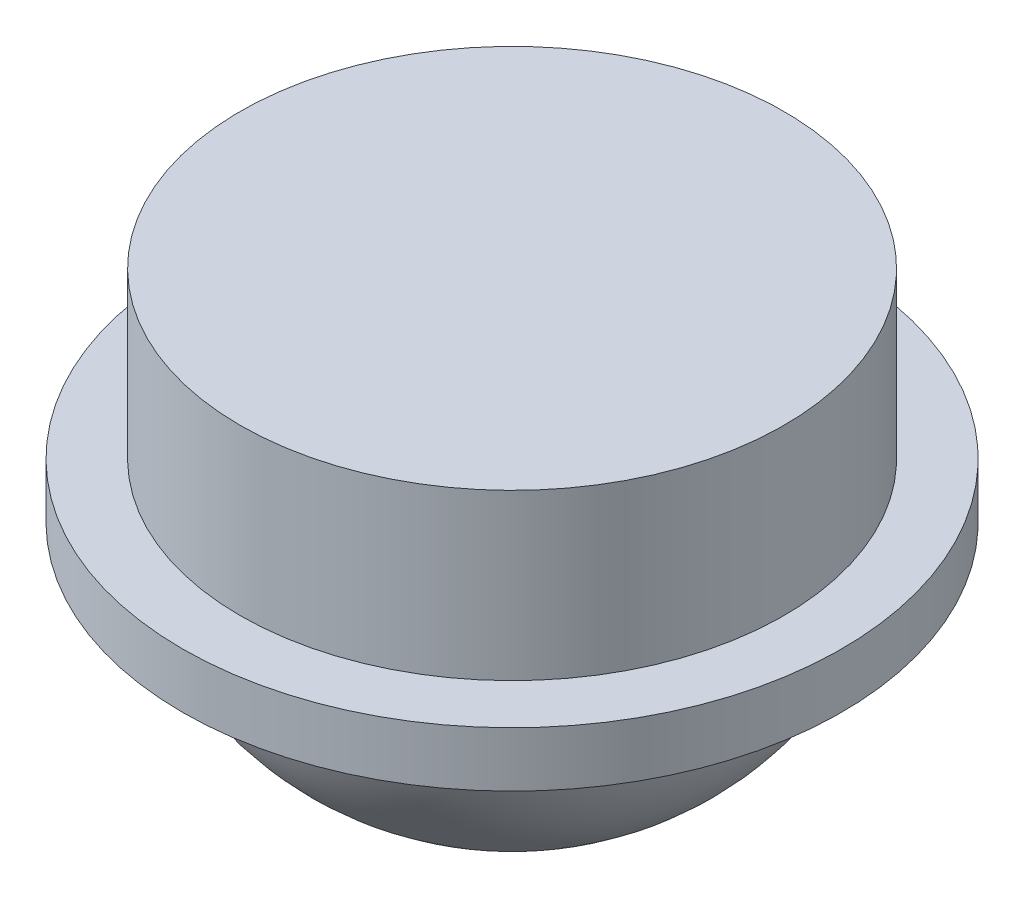
SolidWorks part; units mm, degrees
ref_plane "Front Plane" through (0, 0, 0) normal (0, 0, 1) x (1, 0, 0)
ref_plane "Top Plane" through (0, 0, 0) normal (0, 1, 0) x (1, 0, 0)
ref_plane "Right Plane" through (0, 0, 0) normal (1, 0, 0) x (0, 0, -1)
ref_plane "Plane1" through (0, 0, -44.1) normal (0, 0, -1) x (-1, 0, 0)
sketch "Sketch1" plane through (0, 0, -44.1) normal (0, 0, -1) x (-1, 0, 0)
  line L0 (-60.101, -23.2) -> (-60, -23.2)
  line L1 (-60, -23.2) -> (-60, -15.2)
  line L2 (-60, -15.2) -> (-64.95, -15.2)
  line L3 (-64.95, -15.2) -> (-64.95, -18.2)
  line L4 (-64.95, -18.2) -> (-66, -18.2)
  line L5 (-66, -18.2) -> (-66, -19.2)
  line L6 (-66, -19.2) -> (-65, -19.2)
  line L7 (-60, -23.2) -> (-60, -15.2) construction
  arc A0 (-65, -19.2) -> (-60.101, -23.2) centre (-60.101, -18.2) ccw
revolve "Revolve1" add sketch "Sketch1" angle 360 about L7
